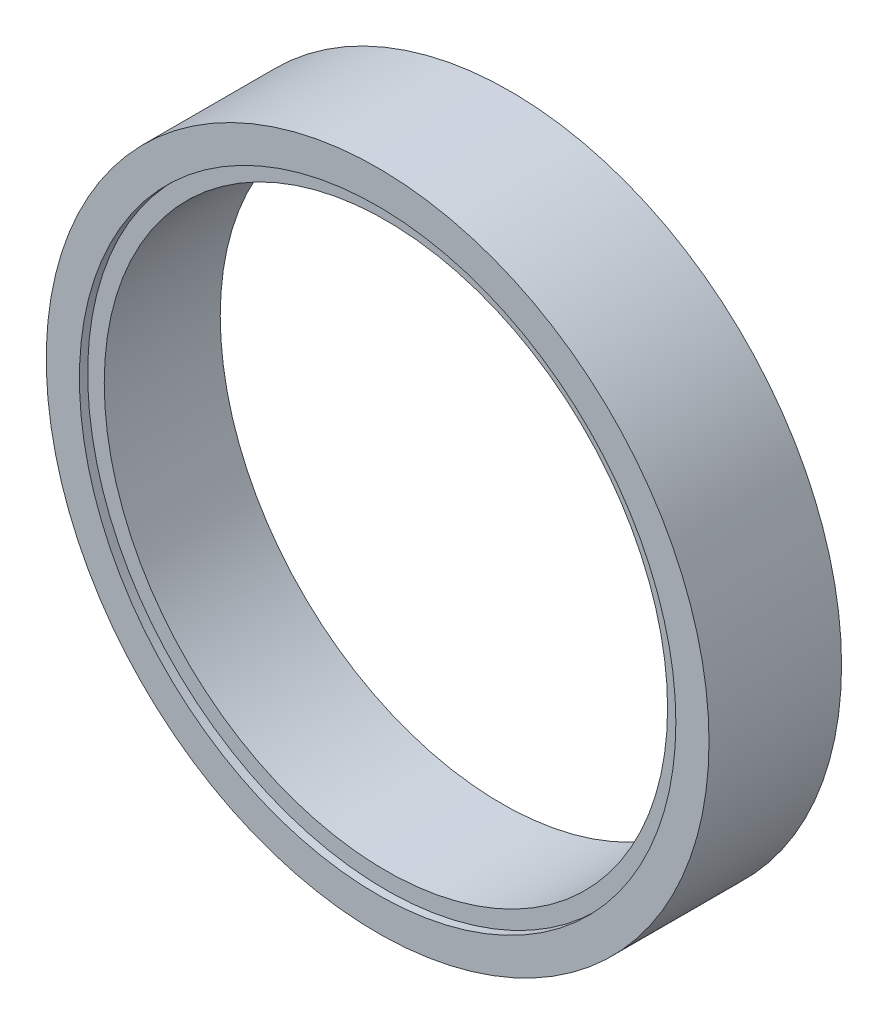
SolidWorks part; units mm, degrees
ref_plane "Front Plane" through (0, 0, 0) normal (0, 0, 1) x (1, 0, 0)
ref_plane "Top Plane" through (0, 0, 0) normal (0, 1, 0) x (1, 0, 0)
ref_plane "Right Plane" through (0, 0, 0) normal (1, 0, 0) x (0, 0, -1)
sketch "Sketch1" plane through (0, 0, 0) normal (0, 0, 1) x (1, 0, 0)
  circle A0 centre (0, 0) radius 63.5
  circle A1 centre (0, 0) radius 53.975
  dimension "D1" = 127
  dimension "D2" = 9.525
extrude "Boss-Extrude1" add sketch "Sketch1" along normal mid plane 25.4
sketch "Sketch2" plane through (0, 0, 12.7) normal (0, 0, 1) x (1, 0, 0)
  circle A3 centre (0, 0) radius 57.15
  circle A4 centre (0, 0) radius 57.15
  dimension "D1" = 3.175
extrude "Cut-Extrude1" cut sketch "Sketch2" against normal blind 1.5875
sketch "Sketch3" plane through (0, 0, -12.7) normal (0, 0, -1) x (-1, 0, 0)
  circle A2 centre (0, 0) radius 57.15
  circle A3 centre (0, 0) radius 57.15
  dimension "D1" = 3.175
extrude "Cut-Extrude2" cut sketch "Sketch3" against normal blind 1.5875
